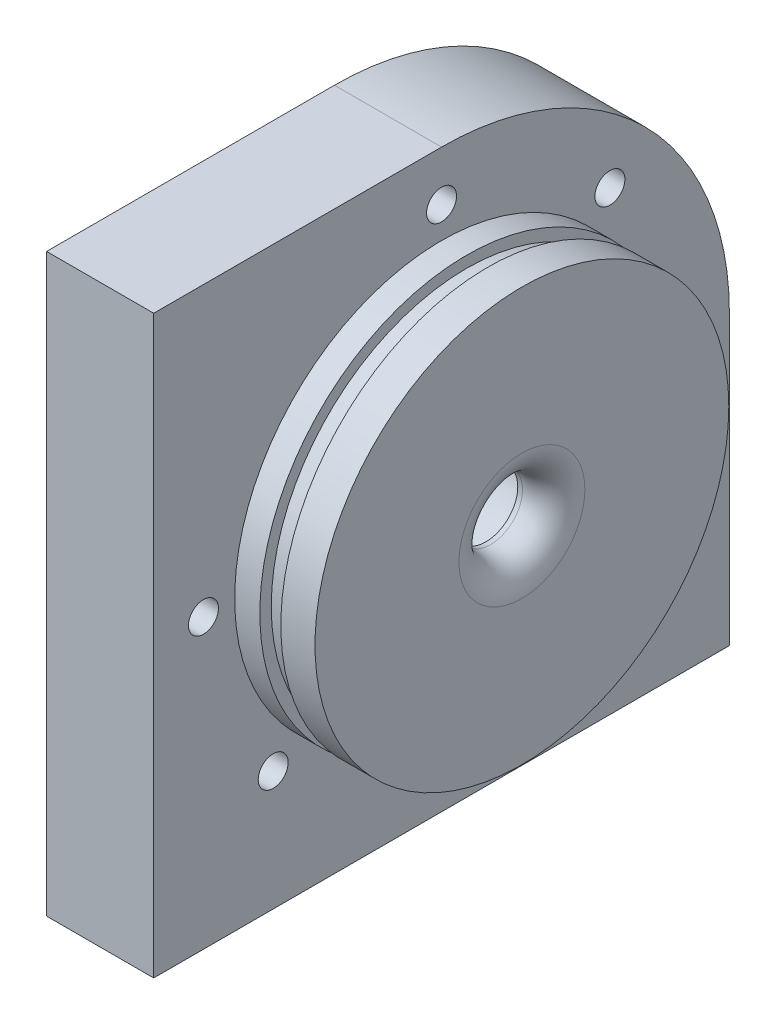
SolidWorks part; units mm, degrees
material "6061 Alloy"
ref_plane "Front Plane" through (0, 0, 0) normal (0, 0, 1) x (1, 0, 0)
ref_plane "Top Plane" through (0, 0, 0) normal (0, 1, 0) x (1, 0, 0)
ref_plane "Right Plane" through (0, 0, 0) normal (1, 0, 0) x (0, 0, -1)
sketch "Sketch1" plane through (0, 0, 0) normal (1, 0, 0) x (0, 0, -1)
  circle A0 centre (0, 0) radius 43.815
extrude "Housing Fitting Extrude" add sketch "Sketch1" along normal blind 17.018
sketch "Sketch2" plane through (0, 0, 0) normal (-1, 0, 0) x (0, 0, 1)
  line L0 (60.96, 0) -> (60.96, 60.96)
  line L1 (60.96, 60.96) -> (0, 60.96)
  line L2 (60.96, 0) -> (60.96, -54.61)
  line L3 (60.96, -60.96) -> (-60.96, -60.96)
  line L7 (0, -55) -> (0, 55) construction
  line L11 (-60.96, 0) -> (-60.96, -54.61)
  line L12 (60.96, -60.96) -> (60.96, -54.61)
  line L13 (-60.96, -60.96) -> (-60.96, -54.61)
  arc A0 (0, 60.96) -> (-60.96, 0) centre (0, 0) ccw
extrude "Housing Body 1" add sketch "Sketch2" along normal blind 22.6822 contours A0 L11 L13 L3 L12 L2 L0 L1
sketch "Sketch3" plane through (17.018, 0, 0) normal (1, 0, 0) x (0, 0, -1)
  circle A0 centre (0, 0) radius 6.731
extrude "Impeller Bore" cut sketch "Sketch3" against normal blind 17.018
sketch "Sketch4" plane through (0, 0, 0) normal (1, 0, 0) x (0, 0, -1)
  circle A0 centre (0, 0) radius 4
extrude "Shaft Bore" cut sketch "Sketch4" against normal blind 70.612
ref_plane "O-Ring Sketch Plane" through (8.509, 0, 0) normal (1, 0, 0) x (0, 0, -1)
sketch "Sketch5" plane through (8.509, 0, 0) normal (1, 0, 0) x (0, 0, -1)
  circle A0 centre (0, 0) radius 43.942
  circle A1 centre (0, 0) radius 41.402
extrude "O-Ring Cut" cut sketch "Sketch5" against normal blind 3.175 and the other way blind 1.27
sketch "Sketch8" plane through (-22.6822, 0, 0) normal (-1, 0, 0) x (0, 0, 1)
  circle A1 centre (52.959, 0) radius 3.175
extrude "Fastening Bore" [suppressed] cut sketch "Sketch8" against normal blind 19.05
sketch "Sketch10" plane through (0, 0, 60.96) normal (0, 0, 1) x (1, 0, 0)
  line L0 (0, -60.96) -> (0, 60.96) construction
  line L1 (-22.6822, 60.96) -> (0, 60.96)
  line L2 (-22.6822, 60.96) -> (-22.6822, 10.16)
  line L3 (-22.6822, 10.16) -> (0, 10.16)
  line L4 (0, 60.96) -> (0, 10.16)
extrude "Discharge Cut" [suppressed] cut sketch "Sketch10" against normal blind 10.541
sketch "Sketch12" plane through (0, 0, 0) normal (1, 0, 0) x (0, 0, -1)
  circle A0 centre (-50.419, 0) radius 3.175
extrude "Cut-Extrude2" cut sketch "Sketch12" against normal blind 19.05
pattern_circular "CirPattern1" count 8 over 360 about axis through (0, 0, 0) along (1, 0, 0) skipping 7 of "Cut-Extrude2"
sketch "Sketch13" plane through (0, 0, 60.96) normal (0, 0, 1) x (1, 0, 0)
  circle A1 centre (-9.525, -41.8177) radius 3.175
extrude "Cut-Extrude3" [suppressed] cut sketch "Sketch13" against normal blind 16.51
sketch "Sketch14" plane through (0, -60.96, 0) normal (0, -1, 0) x (1, 0, 0)
  circle A0 centre (-9.525, -46.7543) radius 3.175
  circle A1 centre (-9.525, 41.9141) radius 3.3928
extrude "Cut-Extrude4" cut sketch "Sketch14" against normal blind 16.51
sketch "Sketch15" plane through (0, 0, -60.96) normal (0, 0, -1) x (-1, 0, 0)
  circle A0 centre (9.525, -39.3375) radius 3.175
extrude "Cut-Extrude5" cut sketch "Sketch15" against normal blind 10.922
fillet "Fillet1" radius 6.604 1 edges at (17.018, 0, -6.731)
sketch "Sketch16" plane through (-22.6822, 0, 0) normal (-1, 0, 0) x (0, 0, 1)
  circle A0 centre (0, 0) radius 11.811
  dimension "D1" = 23.622
extrude "Cut-Extrude7" cut sketch "Sketch16" against normal blind 32.0929
sketch "Sketch17" plane through (-22.6822, 0, 0) normal (-1, 0, 0) x (0, 0, 1)
  circle A0 centre (0, 0) radius 19.558
  dimension "D1" = 39.116
extrude "Cut-Extrude8" cut sketch "Sketch17" against normal blind 13.0429
sketch "Sketch18" plane through (0, 60.96, 0) normal (0, 1, 0) x (1, 0, 0)
  circle A0 centre (-13.4538, -7.8664) radius 0.7265
extrude "Cut-Extrude9" [suppressed] cut sketch "Sketch18" against normal blind 58.166
sketch "Sketch19" plane through (0, 60.96, 0) normal (0, 1, 0) x (1, 0, 0)
  circle A0 centre (-13.2089, -8.2248) radius 4.7625
extrude "Cut-Extrude10" [suppressed] cut sketch "Sketch19" against normal blind 7.62
equation "\"D1@Housing Body 1\"=1.563-0.67"
equation "\"D1@Cut-Extrude7\"=0.2+0.3135+0.750"
equation "\"D1@Sketch17\"=0.93+0.6+0.010"
equation "\"D1@Cut-Extrude8\"=0.2+0.3135"
